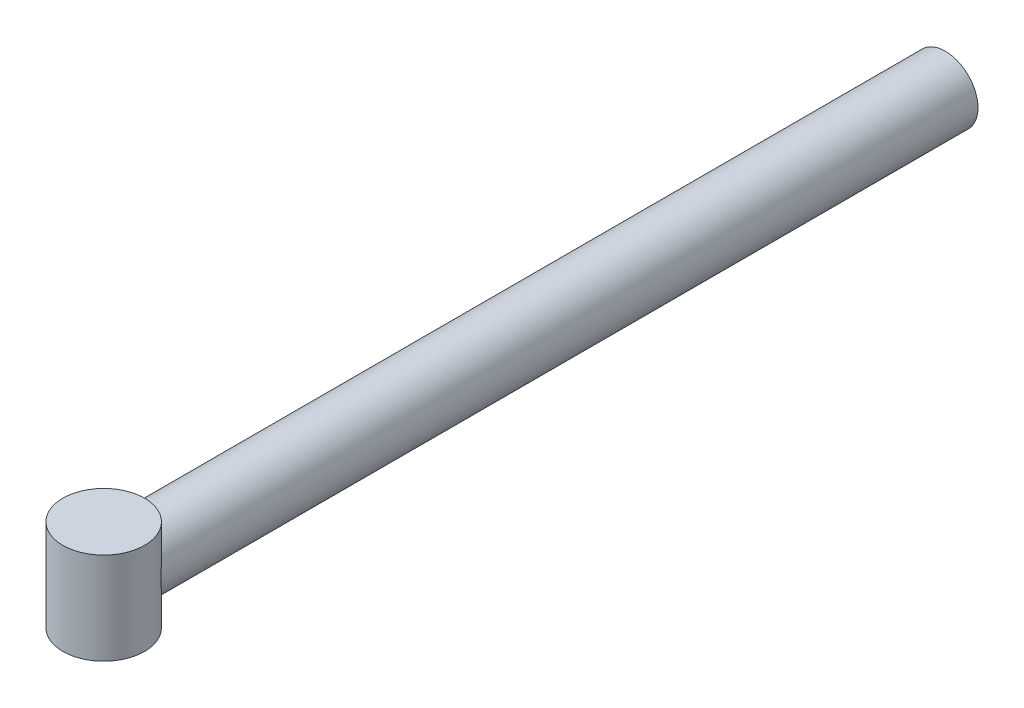
SolidWorks part; units mm, degrees
material "custom standard carbon fiber"
ref_plane "Front Plane" through (0, 0, 0) normal (0, 0, 1) x (1, 0, 0)
ref_plane "Top Plane" through (0, 0, 0) normal (0, 1, 0) x (1, 0, 0)
ref_plane "Right Plane" through (0, 0, 0) normal (1, 0, 0) x (0, 0, -1)
sketch "Sketch2" plane through (0, 0, 0) normal (0, 0, 1) x (1, 0, 0)
  circle A0 centre (0, 0) radius 7
  circle A1 centre (0, 0) radius 8
  dimension "D1" = 16
  dimension "D2" = 14
extrude "Boss-Extrude1" add sketch "Sketch2" along normal blind 196
sketch "Sketch3" plane through (0, 0, 196) normal (0, 0, 1) x (1, 0, 0)
  circle A0 centre (0, 0) radius 8
extrude "Boss-Extrude2" add sketch "Sketch3" along normal blind 4
sketch "Sketch6" plane through (0, 0, 0) normal (0, 1, 0) x (1, 0, 0)
  line L0 (-8, -200) -> (8, -200) construction
  circle A0 centre (0, -206) radius 10
  dimension "D1" = 20
  dimension "D2" = 6
extrude "Boss-Extrude3" add sketch "Sketch6" along normal mid plane 22.5 contours A0
